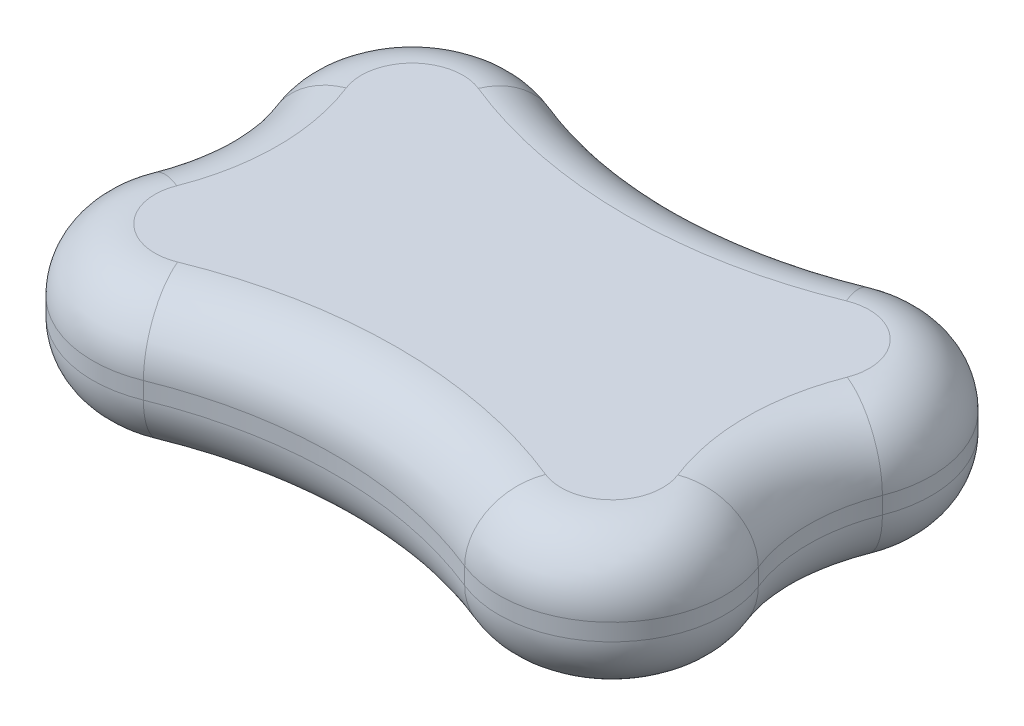
SolidWorks part; units mm, degrees
ref_plane "Front Plane" through (0, 0, 0) normal (0, 0, 1) x (1, 0, 0)
ref_plane "Top Plane" through (0, 0, 0) normal (0, 1, 0) x (1, 0, 0)
ref_plane "Right Plane" through (0, 0, 0) normal (1, 0, 0) x (0, 0, -1)
sketch "Sketch1" plane through (0, 0, 0) normal (0, 1, 0) x (1, 0, 0)
  line L0 (0, -62.5) -> (0, 62.5) construction
  line L1 (0, 0) -> (-105, 0) construction
  arc A0 (-56.8483, 73.5998) -> (0, 62.5) centre (0, 213.6258) ccw
  arc A1 (-56.8483, 73.5998) -> (-109.144, 21.9603) centre (-71.8949, 36.5377) ccw
  arc A2 (-109.144, 21.9603) -> (-105, 0) centre (-165.2586, 0) cw
  arc A3 (-56.8483, -73.5998) -> (0, -62.5) centre (0, -213.6258) cw
  arc A4 (-56.8483, -73.5998) -> (-109.144, -21.9603) centre (-71.8949, -36.5377) cw
  arc A5 (-109.144, -21.9603) -> (-105, 0) centre (-165.2586, 0) ccw
  arc A6 (109.144, -21.9603) -> (105, 0) centre (165.2586, 0) cw
  arc A7 (56.8483, -73.5998) -> (109.144, -21.9603) centre (71.8949, -36.5377) ccw
  arc A8 (56.8483, -73.5998) -> (0, -62.5) centre (0, -213.6258) ccw
  arc A9 (109.144, 21.9603) -> (105, 0) centre (165.2586, 0) ccw
  arc A10 (56.8483, 73.5998) -> (109.144, 21.9603) centre (71.8949, 36.5377) cw
  arc A11 (56.8483, 73.5998) -> (0, 62.5) centre (0, 213.6258) cw
  point P3 (0, 0)
  point P16 (-100, 65)
  point P28 (-100, 0)
  point P29 (-102.6662, -8.6245)
  point P30 (0, -50)
  dimension "D3" = 40
  dimension "D1" = 65
  dimension "D5" = 100
  dimension "D2" = 125
  dimension "D4" = 105
extrude "Boss-Extrude1" add sketch "Sketch1" along normal blind 50
fillet "Fillet1" radius 22 16 edges at (105, 0, 0) (100, 0, -65) (0, 0, -62.5) (-100, 0, -65) (-105, 0, 0) (-100, 0, 65) (0, 0, 62.5) (100, 0, 65) (-100, 50, 65) (-105, 50, 0) (-100, 50, -65) (0, 50, -62.5) (100, 50, -65) (105, 50, 0) (100, 50, 65) (0, 50, 62.5)
